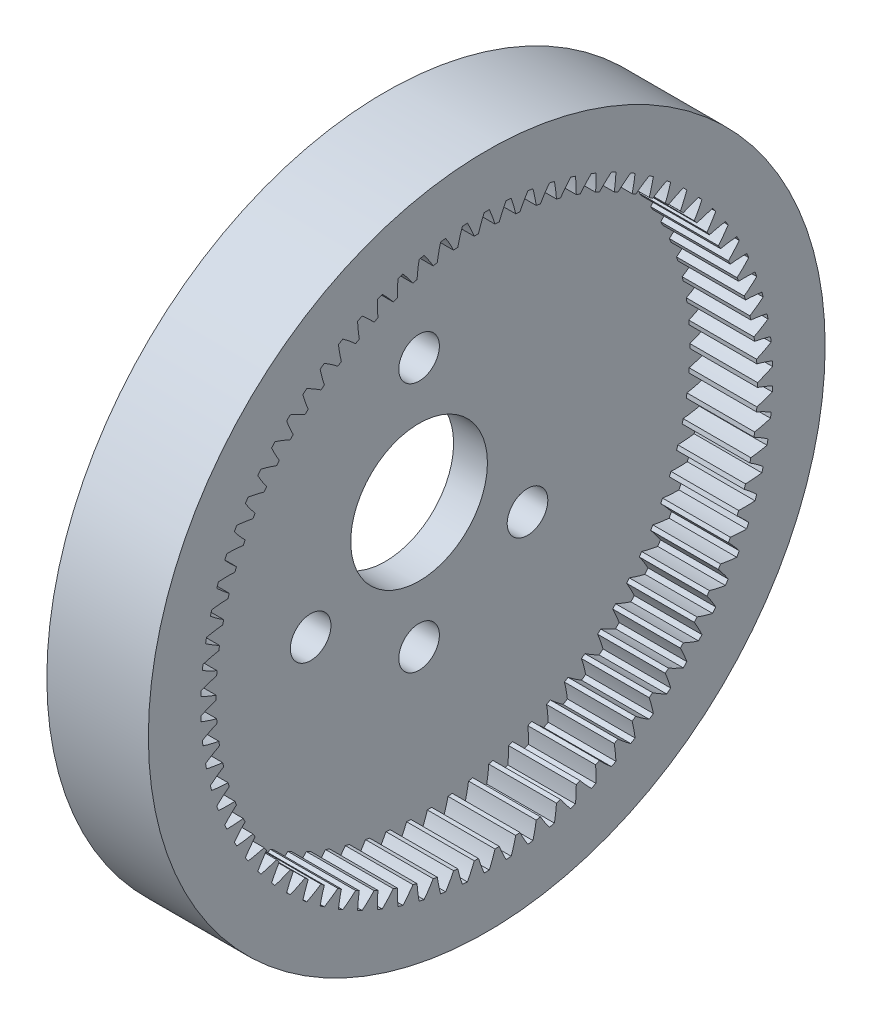
SolidWorks part; units mm, degrees
ref_plane "Plane1" through (0, 0, 0) normal (0, 0, 1) x (1, 0, 0)
ref_plane "Plane2" through (0, 0, 0) normal (0, 1, 0) x (1, 0, 0)
ref_plane "Plane3" through (0, 0, 0) normal (1, 0, 0) x (0, 0, -1)
other "Configuration Table"
sketch "HoldingSke" plane through (0, 0, 0) normal (0, 1, 0) x (1, 0, 0)
  line L0 (0, 0) -> (0.2783, -1.9805)
  line L1 (-15, 0) -> (100, 0) construction
  line L2 (0, 0) -> (-2.1039, 2.3779)
  line L3 (0, 0) -> (-11.863, 4.5341)
  line L4 (0, 0) -> (1.2019, 8.552)
  line L5 (0, 0) -> (-23.7986, -8.8762)
  line L6 (0, 0) -> (-10.5278, -7.1032)
  line L7 (-2.1039, 2.3779) -> (3.3635, 27.1825)
  line L8 (-76.2, 2.8779) -> (-54.61, 2.8779)
  line L9 (-71.009, 38.7566) -> (-53.1078, 45.2721)
  line L10 (-76.2, 71.12) -> (104.1128, 71.12)
  line L11 (0, 0) -> (-12, 0)
  line L12 (-76.2, 101.6) -> (-76.181, 101.6)
  line L13 (24.9733, 27.94) -> (52.9518, 28.4284)
  line L14 (24.9733, 27.94) -> (24.9743, 27.94)
  line L15 (24.9733, 27.94) -> (100.4006, 29.5858)
  circle A0 centre (0, 0) radius 25
  circle A1 centre (0, 0) radius 12.7
  circle A2 centre (0, 0) radius 12.7
  dimension "MHD" = 25.4
  dimension "Hub_dia" = 25.4
  dimension "Diameter" = 50
  dimension "Num_teeth" = 82
  dimension "Pitch" = 2
  dimension "Overall_len" = 25.4
  dimension "Show_teeth" = 82
  dimension "Thickness" = 12.7
  dimension "OAL" = 25.4001
  dimension "T_dim" = 21.59
  dimension "Ap" = 20
  dimension "H" = 19.05
  dimension "Pitch_radius" = 180.3128
  dimension "Width" = 12
  dimension "Backlash" = 0.019
  dimension "Addendum_fac" = 1
  dimension "Dedendum_fac" = 1.25
  dimension "Clearance_fac" = 0.25
  dimension "Dedendum_add" = 0.001
  dimension "Module" = 0.5
sketch "BasProSke" plane through (0, 0, 0) normal (0, 1, 0) x (1, 0, 0)
  line L0 (-10, 0) -> (60, 0) construction
  line L1 (0, 20) -> (0, 25)
  line L2 (0, 20) -> (12, 20)
  line L3 (12, 20) -> (12, 25)
  line L4 (12, 25) -> (0, 25)
  dimension "Diameter" = 50
  dimension "Thickness" = 12
  dimension "Inside_diameter" = 40
revolve "Base-Revolve" add sketch "BasProSke" angle 360 about L0
sketch "TooCutSke" plane through (0, 0, 0) normal (1, 0, 0) x (0, 0, -1)
  line L3 (0.4402, 20.4953) -> (0.4402, 53.6633) construction
  line L4 (0, 0) -> (0, 59.563) construction
  line L5 (0, 0) -> (-2.6171, 68.2774) construction
  line L6 (-9.1946, 16.9976) -> (37.151, 18.7741) construction
  circle A0 centre (0, 0) radius 20.5 construction
  circle A1 centre (0, 0) radius 21.126 construction
  circle A2 centre (0, 0) radius 17.3373 construction
  circle A3 centre (0, 0) radius 19.9746 construction
  arc A4 (0.6164, 19.9651) -> (0.1876, 21.1252) centre (-9.1946, 16.9976) ccw
  arc A5 (0.6164, 19.9651) -> (-0.6164, 19.9651) centre (0, 0) ccw
  arc A6 (0.1876, 21.1252) -> (-0.1876, 21.1252) centre (0, 0) ccw
  arc A7 (-0.1876, 21.1252) -> (-0.6164, 19.9651) centre (9.1946, 16.9976) ccw
  dimension "Pitch_dia" = 41
  dimension "Base_dia" = 34.6747
  dimension "Root_dia" = 42.252
  dimension "Overcut_dia" = 39.9492
  dimension "Flank_rad" = 10.25
  dimension "Half_ang" = 2.195
  dimension "Half_CT" = 0.4402
extrude "ToothCut" cut sketch "TooCutSke" along normal through all
fillet "Breaks" [suppressed] radius 0.05
fillet "RootFillets" [suppressed] radius 0.126
pattern_circular "TeethCuts" count 82 over 360 about axis through (0, 0, 0) along (1, 0, 0) of "RootFillets", "Breaks", "ToothCut"
sketch "Sketch2" plane through (0, 0, 0) normal (-1, 0, 0) x (0, 0, 1)
  circle A0 centre (0, 0) radius 25
extrude "Boss-Extrude1" add sketch "Sketch2" along normal blind 2.5
sketch "Sketch3" plane through (-2.5, 0, 0) normal (-1, 0, 0) x (0, 0, 1)
  line L0 (0, -9.25) -> (0, 9.25) construction
  line L1 (-8.0107, -4.625) -> (0, 0) construction
  line L2 (0, 0) -> (8.0107, -4.625) construction
  circle A0 centre (0, 0) radius 9.25 construction
  circle A1 centre (0, 0) radius 5.05
  circle A2 centre (0, 9.25) radius 1.5
  circle A3 centre (0, -9.25) radius 1.5
  circle A4 centre (8.0107, -4.625) radius 1.5
  circle A5 centre (-8.0107, -4.625) radius 1.5
  dimension "D1" = 18.5
  dimension "D2" = 10.1
  dimension "D3" = 3
  dimension "D4" = 60
  dimension "D5" = 60
extrude "Cut-Extrude1" cut sketch "Sketch3" against normal blind 2.5 and the other way through all
sketch "Sketch4" plane through (12, 0, 0) normal (1, 0, 0) x (0, 0, -1)
  circle A0 centre (0, 0) radius 25
extrude "Cut-Extrude2" cut sketch "Sketch4" against normal blind 7
equation "' \"Module@HoldingSke\" = 6.35"
equation "' \"Num_teeth@HoldingSke\" = 24"
equation "' \"Ap@HoldingSke\" =  14.5"
equation "' \"Ap@HoldingSke\" = 14.5"
equation "' \"Width@HoldingSke\" = 12"
equation "' \"Diameter@HoldingSke\" = 8 * 25.4"
equation "' \"Show_teeth@HoldingSke\" = 100"
equation "' \"Backlash@HoldingSke\" = 0.009 * 25.4"
equation "' \"Addendum_fac@HoldingSke\" = 1.0"
equation "' \"Dedendum_fac@HoldingSke\" = 1.25"
equation "' \"Dedendum_add@HoldingSke\" = 0.00005 * 25.4"
equation "' \"Clearance_fac@HoldingSke\" = 0.25"
equation "\"Pitch@HoldingSke\" = 1 / \"Module@HoldingSke\" "
equation "\"Overcut_dia@TooCutSke\" = (\"Num_teeth@HoldingSke\" - 2 * \"Addendum_fac@HoldingSke\") / \"Pitch@HoldingSke\" - 0.002 * 25.4"
equation "\"Pitch_dia@TooCutSke\" = \"Num_teeth@HoldingSke\" / \"Pitch@HoldingSke\""
equation "\"Base_dia@TooCutSke\" = \"Num_teeth@HoldingSke\" / \"Pitch@HoldingSke\" * cos((\"Ap@HoldingSke\"  * 3.14159265 / 180)) * 0.90"
equation "\"Root_dia@TooCutSke\" = \"Num_teeth@HoldingSke\"  / \"Pitch@HoldingSke\" + 2 *  \"Dedendum_fac@HoldingSke\"/ \"Pitch@HoldingSke\" + \"Dedendum_add@HoldingSke\" * 2"
equation "\"Half_ang@TooCutSke\" = 180 / \"Num_teeth@HoldingSke\""
equation "\"Half_CT@TooCutSke\" = \"Num_teeth@HoldingSke\" / \"Pitch@HoldingSke\" * sin((3.14159265 / 2 / \"Num_teeth@HoldingSke\")) / 2 + 10 * \"Backlash@HoldingSke\" / 4"
equation "\"Flank_rad@TooCutSke\" = \"Num_teeth@HoldingSke\" / \"Pitch@HoldingSke\" / 4"
equation "\"Radius@RootFillets\"= \"Clearance_fac@HoldingSke\" / \"Pitch@HoldingSke\" + \"Dedendum_add@HoldingSke\""
equation "\"Break_rad@Breaks\" = 0.02 / \"Pitch@HoldingSke\" * 5"
equation "\"Num_teeth@TeethCuts\" = int( \"Show_teeth@HoldingSke\" ) + 1"
equation "\"Num_teeth@TeethCuts\" = ((sgn( \"Num_teeth@TeethCuts\" - \"Num_teeth@HoldingSke\" )-1)*( \"Num_teeth@TeethCuts\" - \"Num_teeth@HoldingSke\" ))/-2+ \"Num_teeth@HoldingSke\""
equation "\"Num_teeth@TeethCuts\" = ((sgn( \"Num_teeth@TeethCuts\" - 2.0)+1)*( \"Num_teeth@TeethCuts\" - 2.0))/2 +2.0"
equation "\"Angle@TeethCuts\" = 360.0 / \"Num_teeth@HoldingSke\""
equation "\"Diameter@BasProSke\" = \"Num_teeth@HoldingSke\"  / \"Pitch@HoldingSke\" + 2 *  \"Dedendum_fac@HoldingSke\"/ \"Pitch@HoldingSke\" + \"Dedendum_add@HoldingSke\" * 2 + 0.002 * 25.4"
equation "\"Diameter@BasProSke\" = ((sgn( \"Diameter@BasProSke\"  - \"Diameter@HoldingSke\" )+1)*( \"Diameter@BasProSke\"  - \"Diameter@HoldingSke\" ))/2 + \"Diameter@HoldingSke\""
equation "\"Inside_diameter@BasProSke\" =  (\"Num_teeth@HoldingSke\" - 2 * \"Addendum_fac@HoldingSke\") / \"Pitch@HoldingSke\" "
equation "\"Thickness@BasProSke\"  = \"Width@HoldingSke\""
